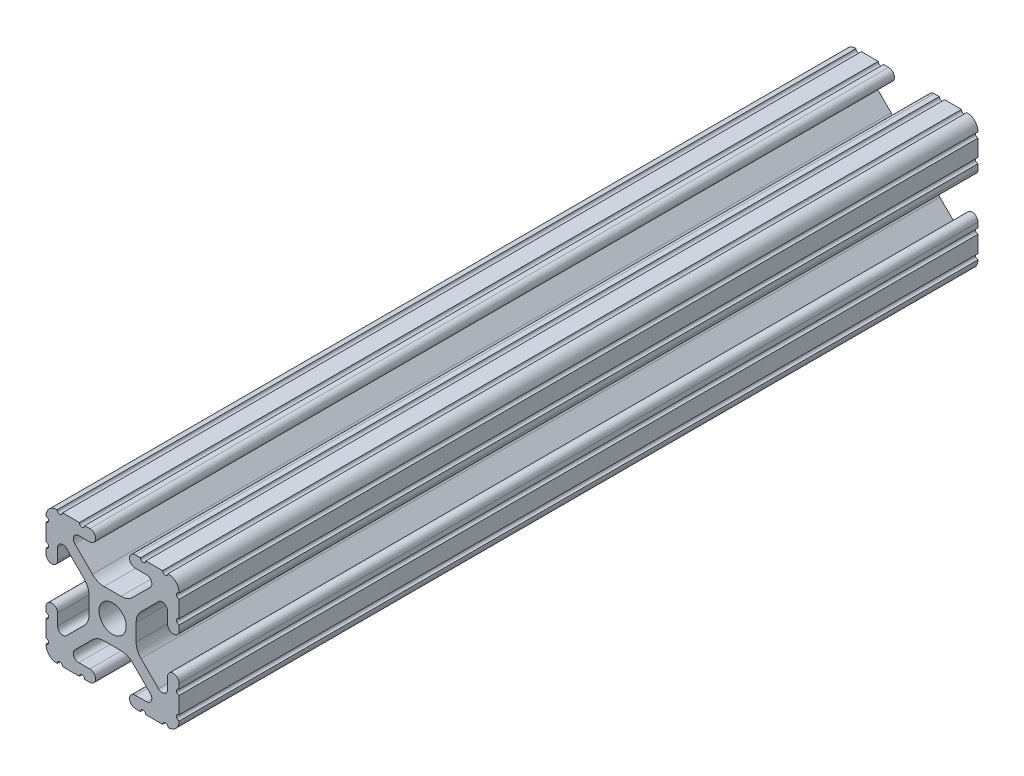
SolidWorks part; units mm, degrees
ref_plane "Front Plane" through (0, 0, 0) normal (0, 0, 1) x (1, 0, 0)
ref_plane "Top Plane" through (0, 0, 0) normal (0, 1, 0) x (1, 0, 0)
ref_plane "Right Plane" through (0, 0, 0) normal (1, 0, 0) x (0, 0, -1)
ref_plane "Plane1" through (0, 0, -25.4) normal (0, 0, -1) x (-1, 0, 0)
sketch "Sketch1" plane through (0, 0, -25.4) normal (0, 0, -1) x (-1, 0, 0)
  line L0 (12.7, -9.5504) -> (12.7, -6.3331)
  line L1 (12.7, -5.3171) -> (12.7, -4.3434)
  line L2 (10.4902, -4.3434) -> (10.4902, -6.4748)
  line L3 (8.7558, -7.1932) -> (5.4257, -3.8632)
  line L4 (4.4958, -1.6181) -> (4.4958, 1.6181)
  line L5 (5.4257, 3.8632) -> (8.7558, 7.1932)
  line L6 (10.4902, 6.4748) -> (10.4902, 4.3434)
  line L7 (12.7, 4.3434) -> (12.7, 5.3171)
  line L8 (12.7, 6.3331) -> (12.7, 9.5504)
  line L9 (9.5504, 12.7) -> (6.3331, 12.7)
  line L10 (5.3171, 12.7) -> (4.3434, 12.7)
  line L11 (4.3434, 10.4902) -> (6.4748, 10.4902)
  line L12 (7.1932, 8.7558) -> (3.8632, 5.4257)
  line L13 (1.6181, 4.4958) -> (-1.6181, 4.4958)
  line L14 (-3.8632, 5.4257) -> (-7.1932, 8.7558)
  line L15 (-6.4748, 10.4902) -> (-4.3434, 10.4902)
  line L16 (-4.3434, 12.7) -> (-5.3171, 12.7)
  line L17 (-6.3331, 12.7) -> (-9.5504, 12.7)
  line L18 (-12.7, 9.5504) -> (-12.7, 6.3331)
  line L19 (-12.7, 5.3171) -> (-12.7, 4.3434)
  line L20 (-10.4902, 4.3434) -> (-10.4902, 6.4748)
  line L21 (-8.7558, 7.1932) -> (-5.4257, 3.8632)
  line L22 (-4.4958, 1.6181) -> (-4.4958, -1.6181)
  line L23 (-5.4257, -3.8632) -> (-8.7558, -7.1932)
  line L24 (-10.4902, -6.4748) -> (-10.4902, -4.3434)
  line L25 (-12.7, -4.3434) -> (-12.7, -5.3171)
  line L26 (-12.7, -6.3331) -> (-12.7, -9.5504)
  line L27 (-9.5504, -12.7) -> (-6.3331, -12.7)
  line L28 (-5.3171, -12.7) -> (-4.3434, -12.7)
  line L29 (-4.3434, -10.4902) -> (-6.4748, -10.4902)
  line L30 (-7.1932, -8.7558) -> (-3.8632, -5.4257)
  line L31 (-1.6181, -4.4958) -> (1.6181, -4.4958)
  line L32 (3.8632, -5.4257) -> (7.1932, -8.7558)
  line L33 (6.4748, -10.4902) -> (4.3434, -10.4902)
  line L34 (4.3434, -12.7) -> (5.3171, -12.7)
  line L35 (6.3331, -12.7) -> (9.5504, -12.7)
  arc A0 (12.6998, -10.5664) -> (12.7, -9.5504) centre (12.7, -10.0584) cw
  arc A1 (12.7, -6.3331) -> (12.7, -5.3171) centre (12.7, -5.8251) cw
  arc A2 (12.7, -4.3434) -> (10.4902, -4.3434) centre (11.5951, -4.3434) ccw
  arc A3 (10.4902, -6.4748) -> (8.7558, -7.1932) centre (9.4742, -6.4748) cw
  arc A4 (5.4257, -3.8632) -> (4.4958, -1.6181) centre (7.6708, -1.6181) cw
  arc A5 (4.4958, 1.6181) -> (5.4257, 3.8632) centre (7.6708, 1.6181) cw
  arc A6 (8.7558, 7.1932) -> (10.4902, 6.4748) centre (9.4742, 6.4748) cw
  arc A7 (10.4902, 4.3434) -> (12.7, 4.3434) centre (11.5951, 4.3434) ccw
  arc A8 (12.7, 5.3171) -> (12.7, 6.3331) centre (12.7, 5.8251) cw
  arc A9 (12.7, 9.5504) -> (12.6998, 10.5664) centre (12.7, 10.0584) cw
  arc A10 (12.6998, 10.5664) -> (10.5664, 12.6998) centre (10.5918, 10.5918) ccw
  arc A11 (10.5664, 12.6998) -> (9.5504, 12.7) centre (10.0584, 12.7) cw
  arc A12 (6.3331, 12.7) -> (5.3171, 12.7) centre (5.8251, 12.7) cw
  arc A13 (4.3434, 12.7) -> (4.3434, 10.4902) centre (4.3434, 11.5951) ccw
  arc A14 (6.4748, 10.4902) -> (7.1932, 8.7558) centre (6.4748, 9.4742) cw
  arc A15 (3.8632, 5.4257) -> (1.6181, 4.4958) centre (1.6181, 7.6708) cw
  arc A16 (-1.6181, 4.4958) -> (-3.8632, 5.4257) centre (-1.6181, 7.6708) cw
  arc A17 (-7.1932, 8.7558) -> (-6.4748, 10.4902) centre (-6.4748, 9.4742) cw
  arc A18 (-4.3434, 10.4902) -> (-4.3434, 12.7) centre (-4.3434, 11.5951) ccw
  arc A19 (-5.3171, 12.7) -> (-6.3331, 12.7) centre (-5.8251, 12.7) cw
  arc A20 (-9.5504, 12.7) -> (-10.5664, 12.6998) centre (-10.0584, 12.7) cw
  arc A21 (-10.5664, 12.6998) -> (-12.6998, 10.5664) centre (-10.5918, 10.5918) ccw
  arc A22 (-12.6998, 10.5664) -> (-12.7, 9.5504) centre (-12.7, 10.0584) cw
  arc A23 (-12.7, 6.3331) -> (-12.7, 5.3171) centre (-12.7, 5.8251) cw
  arc A24 (-12.7, 4.3434) -> (-10.4902, 4.3434) centre (-11.5951, 4.3434) ccw
  arc A25 (-10.4902, 6.4748) -> (-8.7558, 7.1932) centre (-9.4742, 6.4748) cw
  arc A26 (-5.4257, 3.8632) -> (-4.4958, 1.6181) centre (-7.6708, 1.6181) cw
  arc A27 (-4.4958, -1.6181) -> (-5.4257, -3.8632) centre (-7.6708, -1.6181) cw
  arc A28 (-8.7558, -7.1932) -> (-10.4902, -6.4748) centre (-9.4742, -6.4748) cw
  arc A29 (-10.4902, -4.3434) -> (-12.7, -4.3434) centre (-11.5951, -4.3434) ccw
  arc A30 (-12.7, -5.3171) -> (-12.7, -6.3331) centre (-12.7, -5.8251) cw
  arc A31 (-12.7, -9.5504) -> (-12.6998, -10.5664) centre (-12.7, -10.0584) cw
  arc A32 (-12.6998, -10.5664) -> (-10.5664, -12.6998) centre (-10.5918, -10.5918) ccw
  arc A33 (-10.5664, -12.6998) -> (-9.5504, -12.7) centre (-10.0584, -12.7) cw
  arc A34 (-6.3331, -12.7) -> (-5.3171, -12.7) centre (-5.8251, -12.7) cw
  arc A35 (-4.3434, -12.7) -> (-4.3434, -10.4902) centre (-4.3434, -11.5951) ccw
  arc A36 (-6.4748, -10.4902) -> (-7.1932, -8.7558) centre (-6.4748, -9.4742) cw
  arc A37 (-3.8632, -5.4257) -> (-1.6181, -4.4958) centre (-1.6181, -7.6708) cw
  arc A38 (1.6181, -4.4958) -> (3.8632, -5.4257) centre (1.6181, -7.6708) cw
  arc A39 (7.1932, -8.7558) -> (6.4748, -10.4902) centre (6.4748, -9.4742) cw
  arc A40 (4.3434, -10.4902) -> (4.3434, -12.7) centre (4.3434, -11.5951) ccw
  arc A41 (5.3171, -12.7) -> (6.3331, -12.7) centre (5.8251, -12.7) cw
  arc A42 (9.5504, -12.7) -> (10.5664, -12.6998) centre (10.0584, -12.7) cw
  arc A43 (10.5664, -12.6998) -> (12.6998, -10.5664) centre (10.5918, -10.5918) ccw
  circle A44 centre (0, 0) radius 2.6035
extrude "Boss-Extrude1" add sketch "Sketch1" against normal blind 152.4
